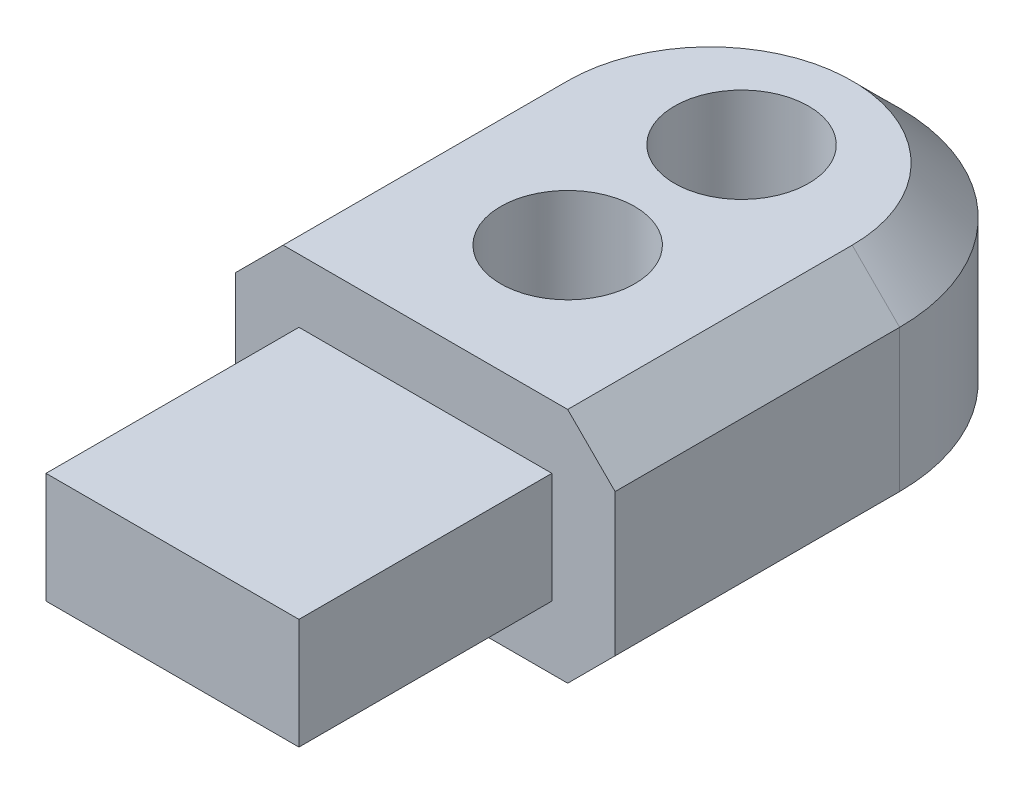
SolidWorks part; units mm, degrees
ref_plane "Front Plane" through (0, 0, 0) normal (0, 0, 1) x (1, 0, 0)
ref_plane "Top Plane" through (0, 0, 0) normal (0, 1, 0) x (1, 0, 0)
ref_plane "Right Plane" through (0, 0, 0) normal (1, 0, 0) x (0, 0, -1)
other "Configuration Table"
sketch "Sketch14" plane through (0, 0, 0) normal (0, 1, 0) x (1, 0, 0)
  line L0 (-2.1722, -29.62) -> (5.8278, -29.62)
  line L7 (5.8278, -37.62) -> (-2.1722, -37.62)
  line L8 (-2.1722, -37.62) -> (-2.1722, -29.62)
  line L13 (5.8278, -29.62) -> (5.8278, -37.62)
  line L14 (3.6744, -19.62) -> (-0.0188, -19.62)
  line L15 (-4.1722, -20.62) -> (7.8278, -20.62)
  line L16 (-4.1722, -20.62) -> (-4.1722, -29.62)
  line L17 (-4.1722, -29.62) -> (7.8278, -29.62)
  line L18 (7.8278, -20.62) -> (7.8278, -29.62)
  arc A0 (7.8278, -20.62) -> (-4.1722, -20.62) centre (1.8278, -20.62) ccw
  point P0 (-55, 0)
  point P4 (55, 0)
  point P7 (0, -55)
  point P9 (0, 55)
  point P10 (-55, 0)
  point P12 (55, 0)
  point P17 (1.8278, -37.62)
  point P20 (0, -55)
  point P23 (0, 55)
  point P24 (-55, 0)
  point P25 (55, 0)
  point P26 (0, -55)
  point P33 (0, 55)
  point P34 (-55, 0)
  point P35 (55, 0)
  point P36 (0, -55)
  point P37 (0, 55)
  dimension "D3" = 8
  dimension "D5" = 1
  dimension "D2" = 8
  dimension "D7" = 12
  dimension "D49" = 9
extrude "Boss-Extrude9" add sketch "Sketch14" along normal blind 3.5 and the other way blind 4
sketch "Sketch16" plane through (0, 0, 29.62) normal (0, 0, 1) x (1, 0, 0)
  line L1 (5.8278, 1.5) -> (-2.1722, 1.5)
  line L2 (5.8278, 1.5) -> (5.8278, -2)
  line L3 (5.8278, -2) -> (-2.1722, -2)
  line L4 (-2.1722, 1.5) -> (-2.1722, -2)
  line L5 (1.8278, -2) -> (1.8278, 1.5) construction
  line L6 (5.8278, -0.25) -> (-2.1722, -0.25) construction
  line L9 (-4.1722, 3.5) -> (7.8278, 3.5) construction
  point P0 (1.8278, -0.25)
  point P6 (1.8278, -2)
  point P11 (1.8278, 3.5)
  dimension "D1" = 8
  dimension "D2" = 3.5
  dimension "D3" = 2
extrude "Boss-Extrude11" add sketch "Sketch16" along normal blind 8
chamfer "Chamfer2" distance 1.5 angle 45 6 edges at (7.8278, 3.5, 25.12) (7.8278, -4, 25.12) (-4.1722, 3.5, 25.12) (-4.1722, -4, 25.12) (1.8278, 3.5, 14.62) (1.8278, -4, 14.62)
sketch "Sketch17" plane through (0, -4, 0) normal (0, -1, 0) x (1, 0, 0)
  line L0 (-2.6722, 29.62) -> (6.3278, 29.62) construction
  line L2 (-2.1722, 37.62) -> (5.8278, 37.62) construction
  line L4 (6.3278, 20.62) -> (7.8278, 20.62) construction
  circle A0 centre (1.8278, 25.12) radius 2.12
  circle A2 centre (1.8278, 19.62) radius 2.12
  point P6 (1.8278, 37.62)
  dimension "D1" = 4.24
  dimension "D2" = 4.5
  dimension "D4" = 1
extrude "Cut-Extrude1" cut sketch "Sketch17" against normal through all both and the other way through all
equation "\"LF\" = 0.06mm"
equation "\"TF\" = 0.04mm"
equation "\"PF\" = 0.1mm"
equation "\"AngLF\" = 0.05deg"
equation "\"AngTF\" = 0.02deg"
equation "\"D1@Sketch17\"=4+4*\"LF\""
